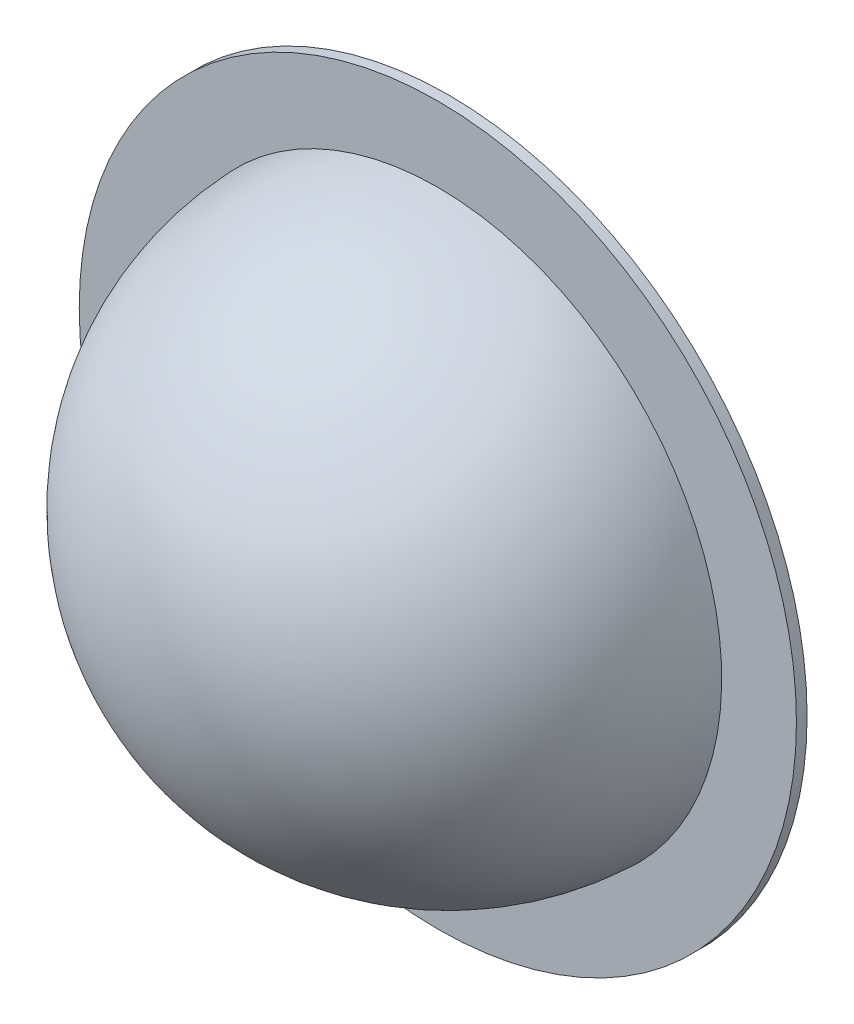
SolidWorks part; units mm, degrees
ref_plane "前视基准面" through (0, 0, 0) normal (0, 0, 1) x (1, 0, 0)
ref_plane "上视基准面" through (0, 0, 0) normal (0, 1, 0) x (1, 0, 0)
ref_plane "右视基准面" through (0, 0, 0) normal (1, 0, 0) x (0, 0, -1)
sketch "草图1" plane through (0, 0, 0) normal (1, 0, 0) x (0, 0, -1)
  line L0 (-40, 0) -> (40, 0)
  arc A0 (40, 0) -> (-40, 0) centre (0, 0) ccw
  dimension "D1" = 80
revolve "旋转1" add sketch "草图1" angle 360 about L0
sketch "草图2" plane through (0, 0, 0) normal (0, 0, 1) x (1, 0, 0)
  circle A0 centre (-18.7622, 13.2377) radius 101.541
extrude "切除-拉伸1" cut sketch "草图2" against normal blind 92
sketch "草图3" plane through (0, 0, 0) normal (0, 1, 0) x (1, 0, 0)
  line L0 (40, 0) -> (-40, 0) construction
  line L1 (0, 38.5) -> (0, -38.5)
  arc A0 (0, -38.5) -> (0, 38.5) centre (0, 0) ccw
  arc A1 (-40, 0) -> (40, 0) centre (0, 0) ccw construction
  dimension "D1" = 1.5
revolve "切除-旋转1" cut sketch "草图3" angle 360 about L1
sketch "草图4" plane through (0, 0, 0) normal (0, 0, -1) x (-1, 0, 0)
  circle A0 centre (0, 0) radius 39
  circle A1 centre (0, 0) radius 60
  dimension "D1" = 120
  dimension "D2" = 78
extrude "凸台-拉伸1" add sketch "草图4" against normal blind 1.5
sketch "草图5" plane through (0, 0, 0) normal (0, 1, 0) x (1, 0, 0)
  line L0 (-45, 0) -> (-45, 2)
  line L1 (-45, 2) -> (-43, 2)
  line L2 (-43, 2) -> (-43, 0)
  line L3 (60, 0) -> (-60, 0) construction
  line L4 (-43, 0) -> (-45, 0)
  line L5 (-60, 0) -> (-60, -1.5) construction
  line L6 (0, 24.6607) -> (0, -55.0563) construction
  dimension "D1" = 2
  dimension "D2" = 2
  dimension "D3" = 15
revolve "旋转2" add sketch "草图5" angle 360 about L6
sketch "草图6" plane through (0, 0, 0) normal (0, 0, -1) x (-1, 0, 0)
  circle A0 centre (0, 0) radius 52.5
  dimension "D1" = 105
extrude "切除-拉伸2" cut sketch "草图6" against normal through all both and the other way through all flip side to cut
sketch "草图7" plane through (0, 0, 1.5) normal (0, 0, 1) x (1, 0, 0)
  circle A0 centre (0, 0) radius 50.5
  dimension "D1" = 101
extrude "切除-拉伸3" cut sketch "草图7" against normal through all both and the other way through all flip side to cut
